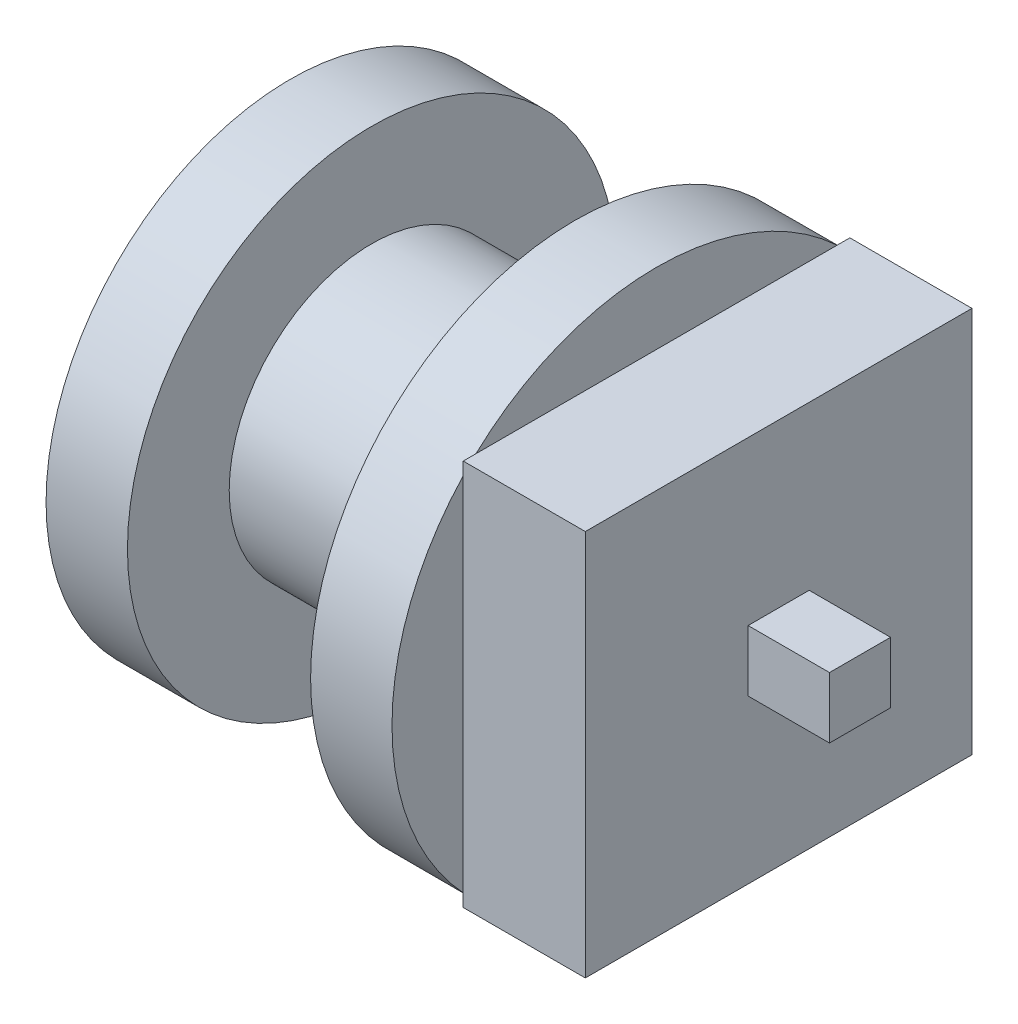
SolidWorks part; units mm, degrees
ref_plane "Front Plane" through (0, 0, 0) normal (0, 0, 1) x (1, 0, 0)
ref_plane "Top Plane" through (0, 0, 0) normal (0, 1, 0) x (1, 0, 0)
ref_plane "Right Plane" through (0, 0, 0) normal (1, 0, 0) x (0, 0, -1)
sketch "Sketch1" plane through (0, 0, 0) normal (1, 0, 0) x (0, 0, -1)
  line L1 (-1.5, 1.5) -> (1.5, 1.5)
  line L2 (-1.5, 1.5) -> (-1.5, -1.5)
  line L3 (-1.5, -1.5) -> (1.5, -1.5)
  line L4 (1.5, 1.5) -> (1.5, -1.5)
  line L5 (-1.5, 1.5) -> (1.5, -1.5) construction
  line L6 (-1.5, -1.5) -> (1.5, 1.5) construction
  point P0 (0, 0)
  dimension "D1" = 3
  dimension "D2" = 3
extrude "Boss-Extrude1" add sketch "Sketch1" along normal blind 4
sketch "Sketch2" plane through (0, 0, 0) normal (-1, 0, 0) x (0, 0, 1)
  line L1 (-9.5, 9.5) -> (9.5, 9.5)
  line L2 (-9.5, 9.5) -> (-9.5, -9.5)
  line L3 (-9.5, -9.5) -> (9.5, -9.5)
  line L4 (9.5, 9.5) -> (9.5, -9.5)
  line L5 (-9.5, 9.5) -> (9.5, -9.5) construction
  line L6 (-9.5, -9.5) -> (9.5, 9.5) construction
  point P0 (0, 0)
  dimension "D1" = 19
  dimension "D2" = 19
extrude "Boss-Extrude2" add sketch "Sketch2" along normal blind 6
sketch "Sketch3" plane through (-6, 0, 0) normal (-1, 0, 0) x (0, 0, 1)
  circle A0 centre (0, 0) radius 13
  dimension "D1" = 26
extrude "Boss-Extrude3" add sketch "Sketch3" along normal blind 4
sketch "Sketch4" plane through (-10, 0, 0) normal (-1, 0, 0) x (0, 0, 1)
  circle A0 centre (0, 0) radius 7
  dimension "D1" = 14
extrude "Boss-Extrude4" add sketch "Sketch4" along normal blind 10
sketch "Sketch5" plane through (-20, 0, 0) normal (-1, 0, 0) x (0, 0, 1)
  circle A0 centre (0, 0) radius 12
  dimension "D1" = 24
extrude "Boss-Extrude5" add sketch "Sketch5" along normal blind 4
sketch "Sketch6" plane through (-24, 0, 0) normal (-1, 0, 0) x (0, 0, 1)
  circle A0 centre (0, 0) radius 5
  dimension "D1" = 10
extrude "Cut-Extrude1" cut sketch "Sketch6" against normal blind 6
